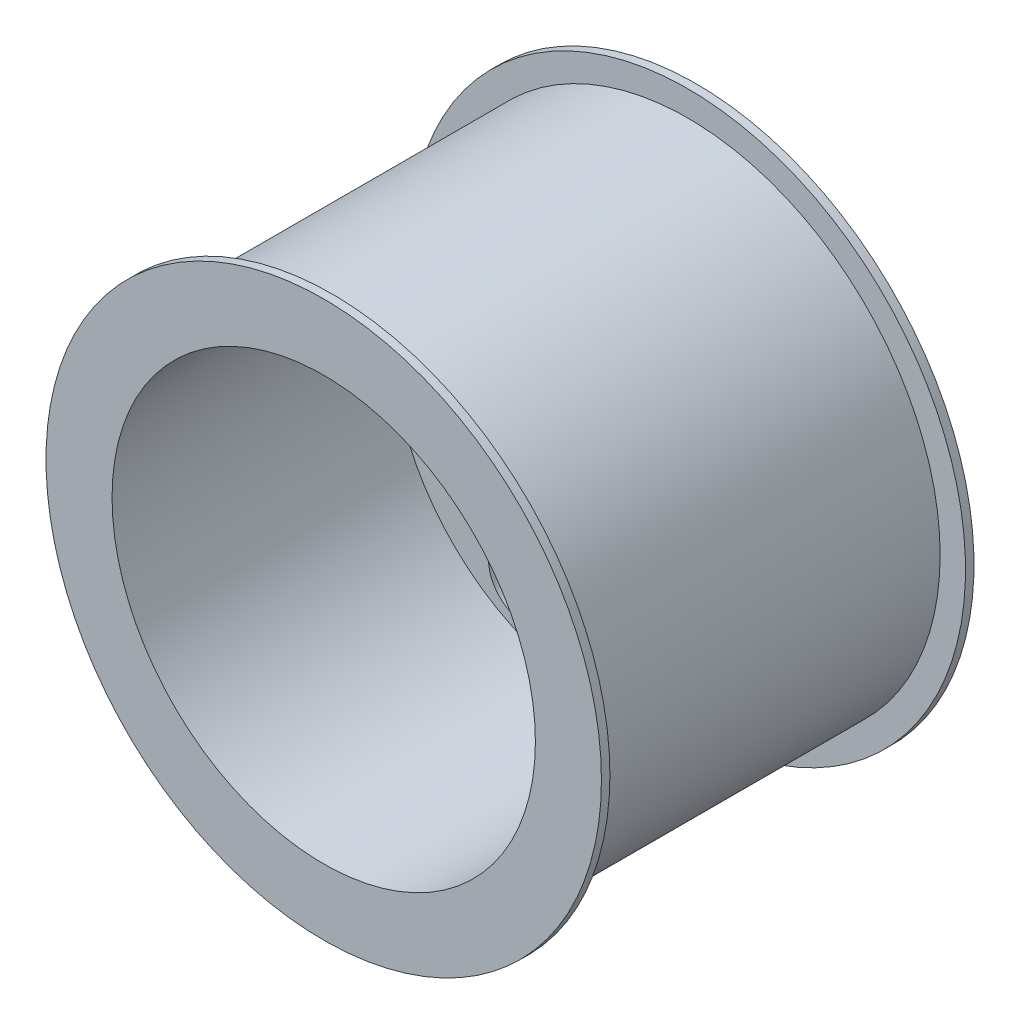
SolidWorks part; units mm, degrees
ref_plane "Front Plane" through (0, 0, 0) normal (0, 0, 1) x (1, 0, 0)
ref_plane "Top Plane" through (0, 0, 0) normal (0, 1, 0) x (1, 0, 0)
ref_plane "Right Plane" through (0, 0, 0) normal (1, 0, 0) x (0, 0, -1)
sketch "Sketch1" plane through (0, 0, 0) normal (0, 0, 1) x (1, 0, 0)
  circle A0 centre (0, 0) radius 32.8
  circle A1 centre (0, 0) radius 25
  dimension "D1" = 65.6
  dimension "D2" = 50
extrude "Boss-Extrude1" add sketch "Sketch1" along normal blind 1
sketch "Sketch2" plane through (0, 0, 1) normal (0, 0, 1) x (1, 0, 0)
  circle A0 centre (0, 0) radius 29.8
  circle A1 centre (0, 0) radius 25
  dimension "D1" = 59.6
extrude "Boss-Extrude2" add sketch "Sketch2" against normal blind 33
sketch "Sketch3" plane through (0, 0, -32) normal (0, 0, -1) x (-1, 0, 0)
  circle A0 centre (0, 0) radius 29.8
extrude "Boss-Extrude3" add sketch "Sketch3" along normal blind 10
sketch "Sketch4" plane through (0, 0, -42) normal (0, 0, -1) x (-1, 0, 0)
  circle A0 centre (0, 0) radius 32.8
extrude "Boss-Extrude4" add sketch "Sketch4" along normal blind 1
sketch "Sketch5" plane through (0, 0, -43) normal (0, 0, -1) x (-1, 0, 0)
  circle A0 centre (0, 0) radius 2.95
  dimension "D1" = 5.9
extrude "Cut-Extrude1" cut sketch "Sketch5" against normal through all
sketch "Sketch6" plane through (0, 0, -43) normal (0, 0, -1) x (-1, 0, 0)
  circle A0 centre (10.3005, 16.4396) radius 4.45
  circle A1 centre (0, 0) radius 2.95 construction
  circle A2 centre (19.3873, -0.7007) radius 4.45
  circle A3 centre (9.0869, -17.1403) radius 4.45
  circle A4 centre (-10.3005, -16.4396) radius 4.45
  circle A5 centre (-19.3873, 0.7007) radius 4.45
  circle A6 centre (-9.0869, 17.1403) radius 4.45
  point P17 (0, 0)
  dimension "D1" = 8.9
  dimension "D2" = 19.4
  dimension "D3" = 6
extrude "Cut-Extrude2" cut sketch "Sketch6" against normal through all
ref_plane "Plane1" through (-25.8076, 14.9, 0) normal (-0.866, 0.5, 0) x (0, 0, 1)
sketch "Sketch7" plane through (-25.8076, 14.9, 0) normal (-0.866, 0.5, 0) x (0, 0, 1)
  line L2 (-43, 32.8) -> (-43, -32.8) construction
  circle A0 centre (-37.1, -1.0178) radius 3
  point P2 (37.1, -7.3111)
  point P3 (37.1, -10.1958)
  point P6 (37.1, 0)
  point P7 (0, 0)
  point P8 (0, 0)
  point P9 (-37.1, -3.2918)
  point P10 (0, 0)
  point P11 (-37.1, -1.0178)
  dimension "D1" = 6
  dimension "D2" = 5.9
extrude "Cut-Extrude3" cut sketch "Sketch7" against normal blind 9.4
sketch "Sketch8" plane through (-17.6669, 10.2, 0) normal (-0.866, 0.5, 0) x (0, 0, 1)
  circle A0 centre (-37.1, -1.0178) radius 2.5
  dimension "D1" = 5
extrude "Cut-Extrude4" cut sketch "Sketch8" against normal blind 21
